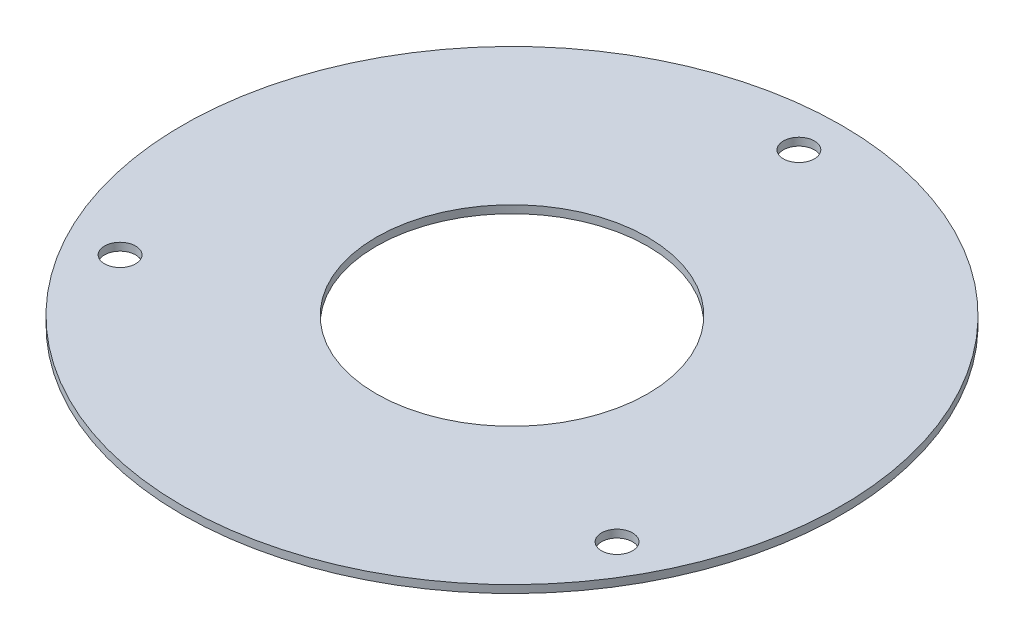
SolidWorks part; units mm, degrees
ref_plane "Front Plane" through (0, 0, 0) normal (0, 0, 1) x (1, 0, 0)
ref_plane "Top Plane" through (0, 0, 0) normal (0, 1, 0) x (1, 0, 0)
ref_plane "Right Plane" through (0, 0, 0) normal (1, 0, 0) x (0, 0, -1)
sketch "Sketch1" plane through (0, 0, 0) normal (0, 1, 0) x (1, 0, 0)
  circle A0 centre (0, 0) radius 17.5
  circle A1 centre (0, 0) radius 42.5
  circle A2 centre (0, 37) radius 2
  circle A3 centre (32.0429, -18.5) radius 2
  circle A4 centre (-32.0429, -18.5) radius 2
  point P12 (0, 0)
  dimension "D1" = 35
  dimension "D2" = 85
  dimension "D3" = 4
  dimension "D4" = 37
  dimension "D5" = 3
extrude "Boss-Extrude1" add sketch "Sketch1" along normal blind 1
sketch "Sketch2" plane through (0, 1, 0) normal (0, 1, 0) x (1, 0, 0)
  line L0 (0, 0) -> (-32.0429, -18.5) construction
